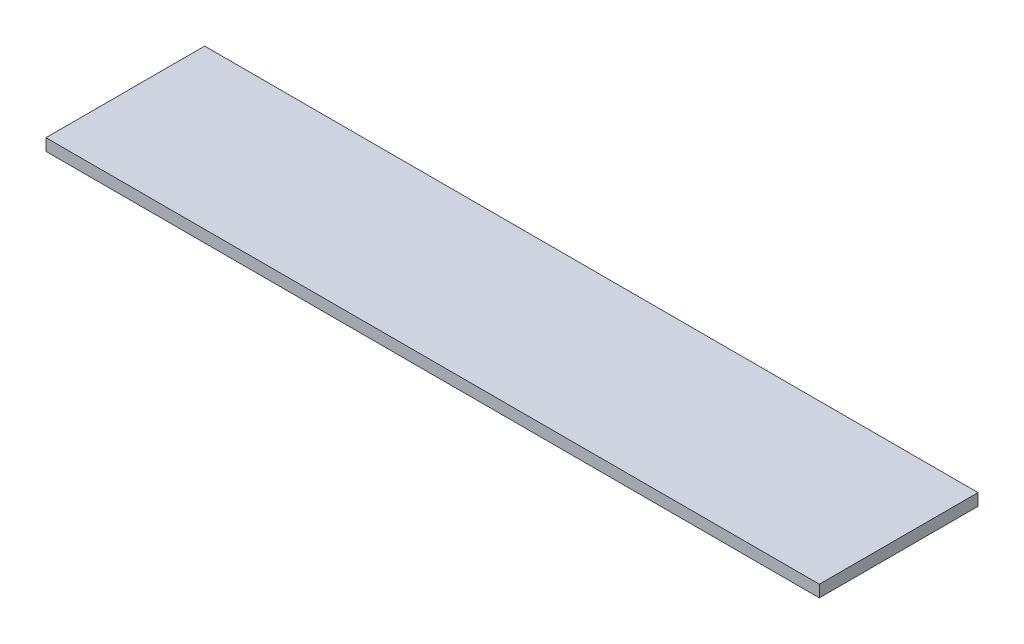
SolidWorks part; units mm, degrees
ref_plane "Alzado" through (0, 0, 0) normal (0, 0, 1) x (1, 0, 0)
ref_plane "Planta" through (0, 0, 0) normal (0, 1, 0) x (1, 0, 0)
ref_plane "Vista lateral" through (0, 0, 0) normal (1, 0, 0) x (0, 0, -1)
sketch "Croquis1" plane through (0, 0, 0) normal (0, 1, 0) x (1, 0, 0)
  line L1 (-585, 120) -> (585, 120)
  line L2 (-585, 120) -> (-585, -120)
  line L3 (-585, -120) -> (585, -120)
  line L4 (585, 120) -> (585, -120)
  line L5 (-585, 120) -> (585, -120) construction
  line L6 (-585, -120) -> (585, 120) construction
  point P0 (0, 0)
  dimension "D1" = 1170
  dimension "D2" = 240
extrude "Saliente-Extruir1" add sketch "Croquis1" along normal blind 18
